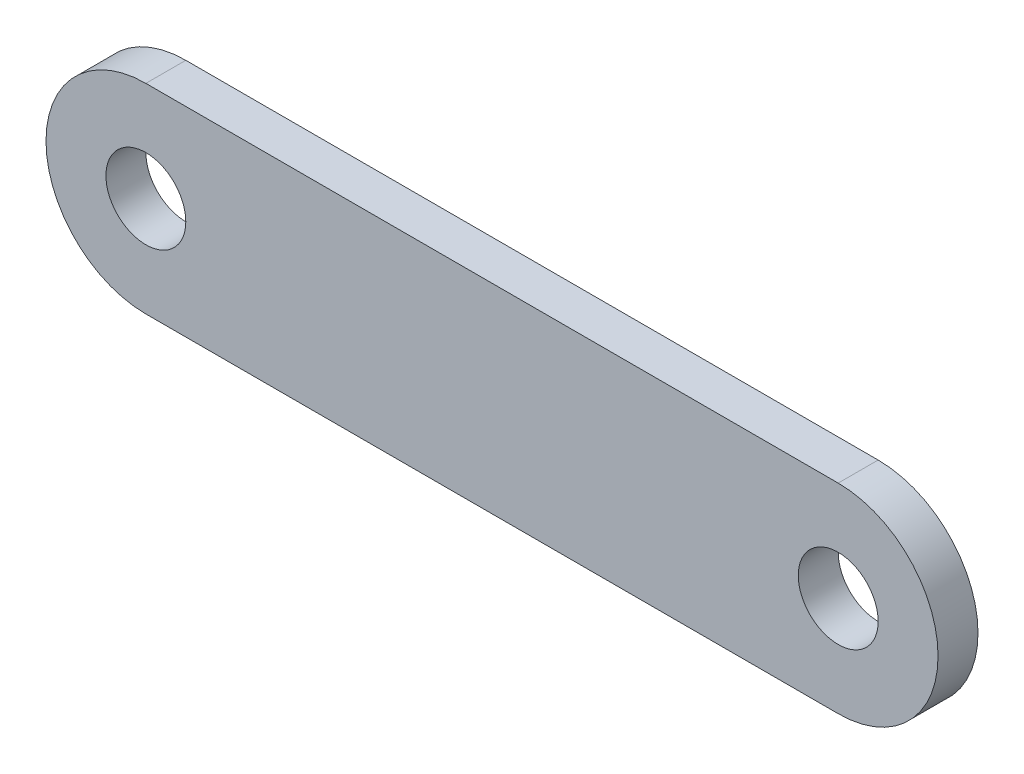
SolidWorks part; units mm, degrees
material "Alliage 1060"
ref_plane "Plan de face" through (0, 0, 0) normal (0, 0, 1) x (1, 0, 0)
ref_plane "Plan de dessus" through (0, 0, 0) normal (0, 1, 0) x (1, 0, 0)
ref_plane "Plan de droite" through (0, 0, 0) normal (1, 0, 0) x (0, 0, -1)
sketch "Esquisse1" plane through (0, 0, 0) normal (0, 0, 1) x (1, 0, 0)
  line L0 (0, 0) -> (26, 0) construction
  line L1 (0, 3.75) -> (26, 3.75)
  line L2 (0, -3.75) -> (26, -3.75)
  arc A0 (0, 3.75) -> (0, -3.75) centre (0, 0) ccw
  arc A1 (26, -3.75) -> (26, 3.75) centre (26, 0) ccw
  circle A2 centre (0, 0) radius 1.5
  circle A3 centre (26, 0) radius 1.5
  point P3 (13, 0)
  dimension "D1" = 3
  dimension "D2" = 26
  dimension "D3" = 7.5
extrude "Boss.-Extru.1" add sketch "Esquisse1" along normal blind 1.5
